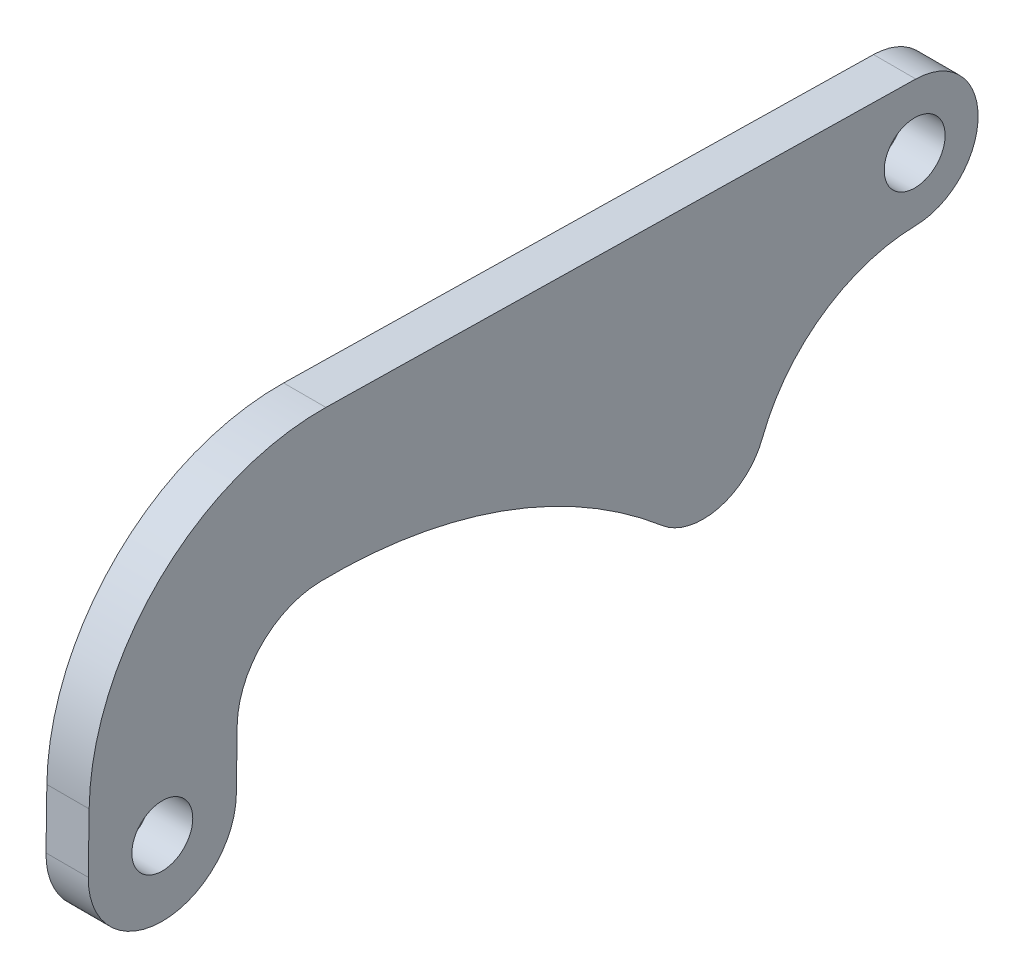
SolidWorks part; units mm, degrees
ref_plane "Front Plane" through (0, 0, 0) normal (0, 0, 1) x (1, 0, 0)
ref_plane "Top Plane" through (0, 0, 0) normal (0, 1, 0) x (1, 0, 0)
ref_plane "Right Plane" through (0, 0, 0) normal (1, 0, 0) x (0, 0, -1)
sketch "Sketch1" plane through (0, 0, 0) normal (1, 0, 0) x (0, 0, -1)
  line L0 (0, 0) -> (56.4713, 16.1581) construction
  line L1 (56.4713, 16.1581) -> (36.2438, 16.1581) construction
  line L2 (-5.5557, 0.0789) -> (-5.4929, 4.4978)
  line L3 (5.5557, -0.0789) -> (5.6184, 4.3401)
  line L4 (56.5563, 20.9198) -> (12.2792, 21.7097)
  line L5 (11.8545, 10.5989) -> (56.5563, 11.3963) construction
  line L6 (36.2438, 11.034) -> (36.2438, 21.2822) construction
  circle A0 centre (0, 0) radius 2.286
  circle A1 centre (56.4713, 16.1581) radius 2.286
  arc A2 (11.8545, 10.5989) -> (5.6184, 4.3401) centre (11.9678, 4.2499) ccw
  arc A3 (-5.5557, 0.0789) -> (5.5557, -0.0789) centre (0, 0) ccw
  arc A4 (56.5563, 11.3963) -> (56.5563, 20.9198) centre (56.4713, 16.1581) ccw
  arc A5 (-5.4929, 4.4978) -> (12.2792, 21.7097) centre (11.9678, 4.2499) cw
  arc A6 (11.8545, 10.5989) -> (37.5097, 1.4187) centre (12.5416, -27.9191) cw
  arc A7 (37.5097, 1.4187) -> (45.0414, 3.3359) centre (40.5963, 5.0456) ccw
  arc A8 (45.0414, 3.3359) -> (56.5563, 11.3963) centre (56.7806, -1.1793) cw
  point P5 (36.2438, 16.1581)
  dimension "D1" = 0.7937
  dimension "D2" = 4.572
  dimension "D3" = 12.7
  dimension "D4" = 9.525
  dimension "D5" = 11.1125
  dimension "D6" = 58.7375
  dimension "D7" = 15.875
  dimension "D9" = 4.7625
  dimension "D11" = 11.1125
  dimension "D8" = 11.1125
  dimension "D10" = 12.7
extrude "Boss-Extrude1" add sketch "Sketch1" along normal mid plane 3.175
